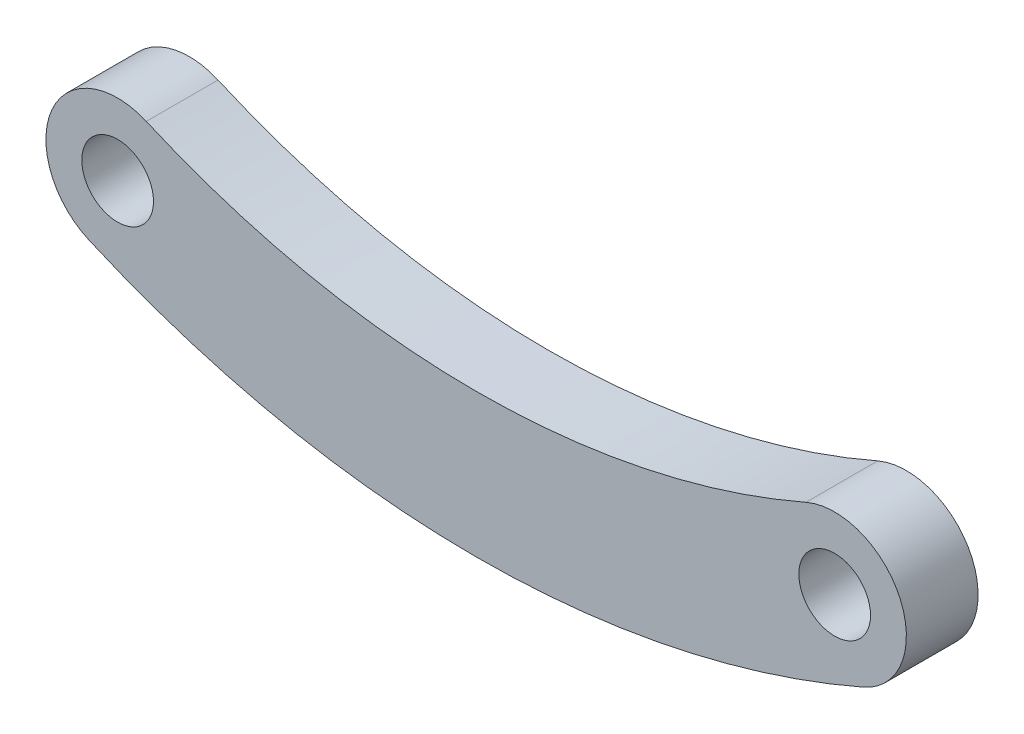
SolidWorks part; units mm, degrees
ref_plane "Front Plane" through (0, 0, 0) normal (0, 0, 1) x (1, 0, 0)
ref_plane "Top Plane" through (0, 0, 0) normal (0, 1, 0) x (1, 0, 0)
ref_plane "Right Plane" through (0, 0, 0) normal (1, 0, 0) x (0, 0, -1)
sketch "Sketch1" plane through (0, 0, 0) normal (0, 0, 1) x (1, 0, 0)
  arc A0 (0, 0) -> (40, 0) centre (20, 45.8258) ccw construction
  arc A1 (-1.6, -3.6661) -> (41.6, -3.6661) centre (20, 45.8258) ccw
  arc A2 (1.6, 3.6661) -> (38.4, 3.6661) centre (20, 45.8258) ccw
  arc A3 (-1.6, -3.6661) -> (1.6, 3.6661) centre (0, 0) cw
  arc A4 (41.6, -3.6661) -> (38.4, 3.6661) centre (40, 0) ccw
  circle A5 centre (0, 0) radius 2
  circle A6 centre (40, 0) radius 2
  dimension "D1" = 40
  dimension "D2" = 50
  dimension "D3" = 4
  dimension "D5" = 4
  dimension "D4" = 4
extrude "Boss-Extrude1" add sketch "Sketch1" along normal blind 4
